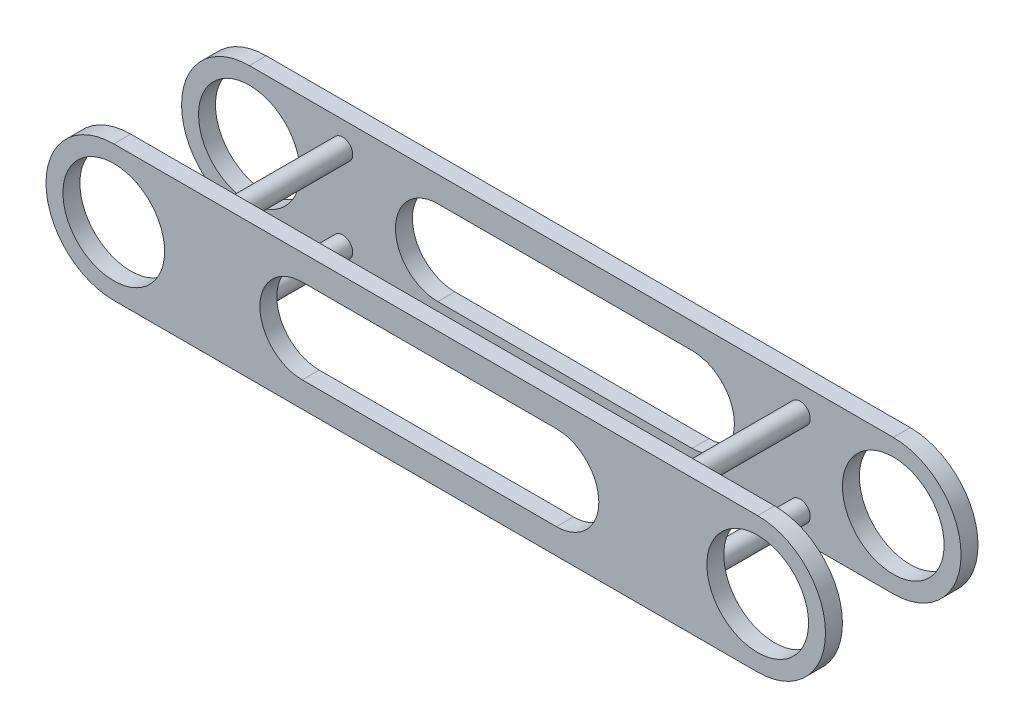
SolidWorks part; units mm, degrees
ref_plane "Front Plane" through (0, 0, 0) normal (0, 0, 1) x (1, 0, 0)
ref_plane "Top Plane" through (0, 0, 0) normal (0, 1, 0) x (1, 0, 0)
ref_plane "Right Plane" through (0, 0, 0) normal (1, 0, 0) x (0, 0, -1)
sketch "Sketch1" plane through (0, 0, 0) normal (0, 0, 1) x (1, 0, 0)
  circle A0 centre (0, 0) radius 30
  dimension "D1" = 60
extrude "Boss-Extrude1" add sketch "Sketch1" along normal mid plane 105
ref_plane "Plane1" through (0, 0, 45) normal (0, 0, 1) x (1, 0, 0)
sketch "Sketch2" plane through (0, 0, 45) normal (0, 0, 1) x (1, 0, 0)
  line L0 (0, 40) -> (0, -40) construction
  line L1 (0, 40) -> (380, 40)
  line L2 (0, 0) -> (380, 0) construction
  line L3 (380, 40) -> (380, -40) construction
  line L4 (0, -40) -> (380, -40)
  arc A0 (0, 40) -> (0, -40) centre (0, 0) ccw
  arc A1 (380, -40) -> (380, 40) centre (380, 0) ccw
  point P6 (0, 0)
  dimension "D1" = 40
  dimension "D2" = 380
extrude "Boss-Extrude2" add sketch "Sketch2" against normal blind 10
sketch "Sketch3" plane through (0, 0, 45) normal (0, 0, 1) x (1, 0, 0)
  line L0 (111.2324, 0) -> (261.2324, 0) construction
  line L1 (111.2324, 25) -> (261.2324, 25)
  line L2 (111.2324, -25) -> (261.2324, -25)
  arc A0 (111.2324, 25) -> (111.2324, -25) centre (111.2324, 0) ccw
  arc A1 (261.2324, -25) -> (261.2324, 25) centre (261.2324, 0) ccw
  point P2 (186.2324, 0)
  dimension "D2" = 25
  dimension "D1" = 150
extrude "Cut-Extrude1" cut sketch "Sketch3" against normal through all
sketch "Sketch4" plane through (0, 0, 0) normal (0, 0, 1) x (1, 0, 0)
  circle A0 centre (380, 0) radius 30
  dimension "D1" = 60
extrude "Boss-Extrude3" add sketch "Sketch4" along normal mid plane 105
mirror "Mirror1" about plane through (0, 0, 0) normal (0, 0, 1) of "Cut-Extrude1", "Boss-Extrude2"
sketch "Sketch5" plane through (0, 0, -45) normal (0, 0, -1) x (-1, 0, 0)
  line L0 (-380, 0) -> (0, 0) construction
  line L1 (-190, 0) -> (-190, -25) construction
  line L2 (-325, 25) -> (-55, 25) construction
  line L3 (-325, 25) -> (-325, -25) construction
  line L4 (-325, -25) -> (-55, -25) construction
  line L5 (-55, 25) -> (-55, -25) construction
  line L6 (-325, 25) -> (-55, -25) construction
  line L7 (-325, -25) -> (-55, 25) construction
  circle A0 centre (-325, 25) radius 6
  circle A1 centre (-325, -25) radius 6
  circle A2 centre (-55, -25) radius 6
  circle A3 centre (-55, 25) radius 6
  point P4 (-190, 0)
  dimension "D3" = 12
  dimension "D1" = 50
  dimension "D2" = 270
extrude "Boss-Extrude4" add sketch "Sketch5" against normal up to surface (80 mm away) up to face at (410, 0, 35)
sketch "Sketch6" plane through (0, 0, -52.5) normal (0, 0, -1) x (-1, 0, 0)
  circle A1 centre (-380, 0) radius 30
  circle A2 centre (-380, 0) radius 30
  circle A3 centre (0, 0) radius 30
  circle A4 centre (0, 0) radius 30
  dimension "D1" = 0
  dimension "D2" = 0
extrude "Cut-Extrude2" cut sketch "Sketch6" against normal through all
